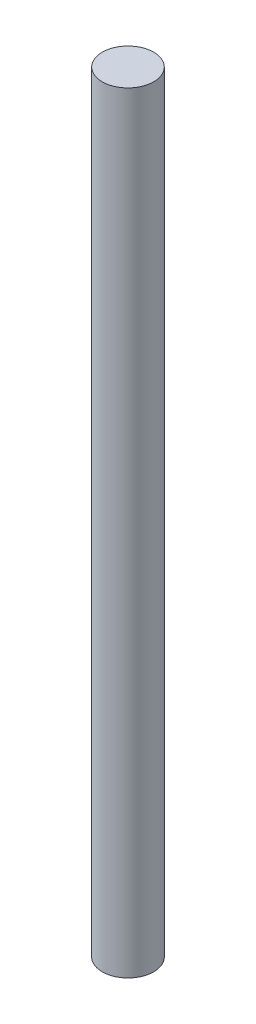
SolidWorks part; units mm, degrees
ref_plane "Front Plane" through (0, 0, 0) normal (0, 0, 1) x (1, 0, 0)
ref_plane "Top Plane" through (0, 0, 0) normal (0, 1, 0) x (1, 0, 0)
ref_plane "Right Plane" through (0, 0, 0) normal (1, 0, 0) x (0, 0, -1)
sketch "Sketch1" plane through (0, 0, 0) normal (0, 1, 0) x (1, 0, 0)
  circle A0 centre (0, 0) radius 4
extrude "Boss-Extrude1" add sketch "Sketch1" along normal blind 120
